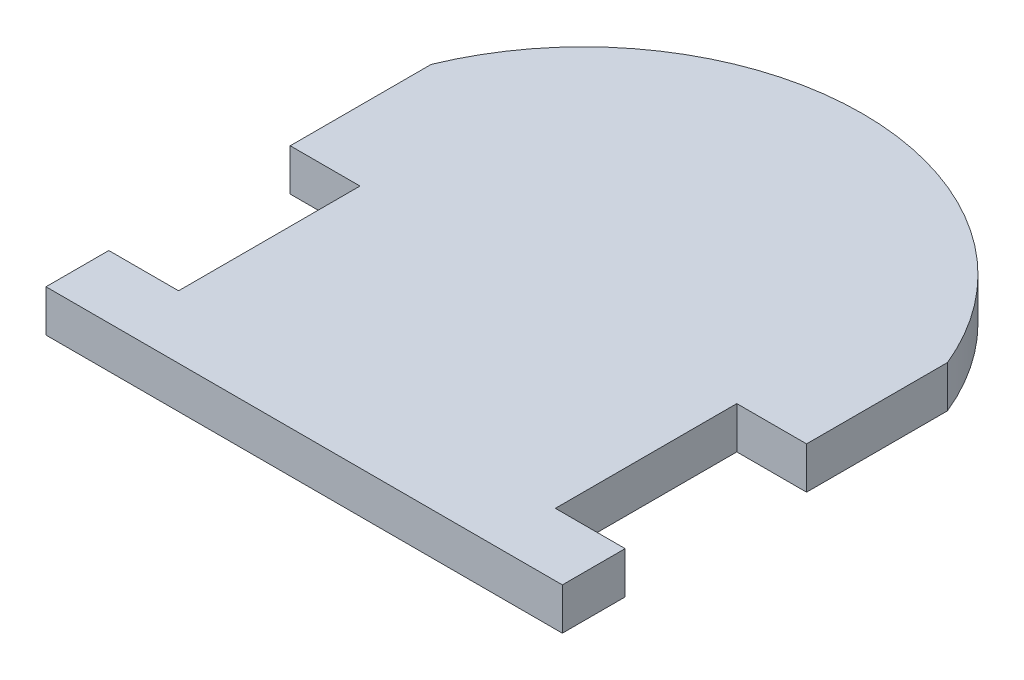
SolidWorks part; units mm, degrees
ref_plane "Front Plane" through (0, 0, 0) normal (0, 0, 1) x (1, 0, 0)
ref_plane "Top Plane" through (0, 0, 0) normal (0, 1, 0) x (1, 0, 0)
ref_plane "Right Plane" through (0, 0, 0) normal (1, 0, 0) x (0, 0, -1)
sketch "Sketch1" plane through (0, 0, 0) normal (0, 1, 0) x (1, 0, 0)
  line L0 (-20, 0) -> (-20, -20)
  line L1 (-20, -20) -> (20, -20)
  line L2 (20, 0) -> (20, -20)
  line L3 (18.5, -20) -> (18.5, 7.5993)
  line L5 (-18.5, 7.5993) -> (-18.5, -20)
  arc A0 (20, 0) -> (-20, 0) centre (0, 0) ccw
  dimension "D1" = 40
  dimension "D2" = 1.5
  dimension "D3" = 1.5
extrude "Boss-Extrude1" add sketch "Sketch1" along normal blind 3 contours L3 A0 L5 L1
sketch "Sketch2" plane through (0, 3, 0) normal (0, 1, 0) x (1, 0, 0)
  line L0 (0, -20) -> (0, 0.4984)
  line L1 (-20, -20) -> (20, -20) construction
  line L3 (20, -20) -> (20, 0) construction
  line L4 (20, -2.5) -> (13.5, -2.5)
  line L5 (13.5, -2.5) -> (13.5, -15.5)
  line L6 (13.5, -15.5) -> (20, -15.5)
  line L8 (-13.5, -15.5) -> (-20, -15.5)
  line L9 (-13.5, -2.5) -> (-13.5, -15.5)
  line L10 (-20, -2.5) -> (-13.5, -2.5)
  line L11 (20, -15.5) -> (20, -2.5)
  line L12 (-20, -15.5) -> (-20, -2.5)
  dimension "D3" = 13.5
extrude "Cut-Extrude2" cut sketch "Sketch2" against normal blind 10
